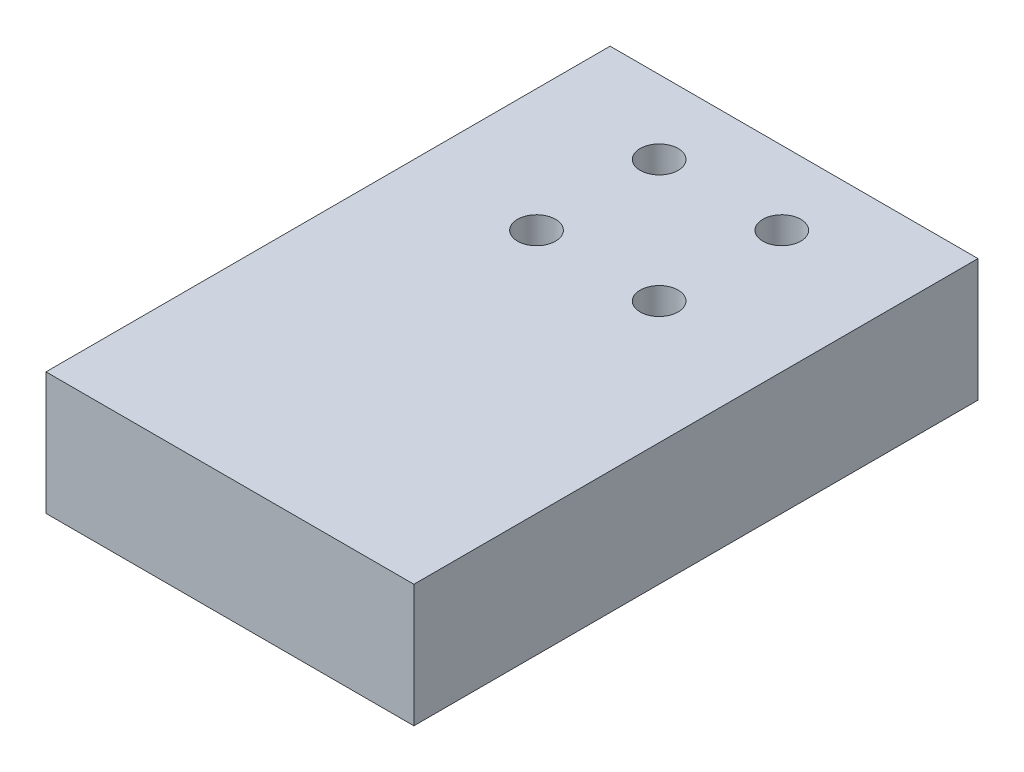
SolidWorks part; units mm, degrees
ref_plane "前视基准面" through (0, 0, 0) normal (0, 0, 1) x (1, 0, 0)
ref_plane "上视基准面" through (0, 0, 0) normal (0, 1, 0) x (1, 0, 0)
ref_plane "右视基准面" through (0, 0, 0) normal (1, 0, 0) x (0, 0, -1)
sketch "草图1" plane through (0, 0, 0) normal (0, 1, 0) x (1, 0, 0)
  line L1 (-15, -15) -> (15, -15)
  line L2 (-15, -15) -> (-15, 15)
  line L3 (-15, 15) -> (15, 15)
  line L4 (15, -15) -> (15, 15)
  line L5 (-15, -15) -> (15, 15) construction
  line L6 (-15, 15) -> (15, -15) construction
  point P0 (0, 0)
  dimension "D1" = 30
  dimension "D2" = 30
extrude "凸台-拉伸1" add sketch "草图1" along normal blind 10
sketch "草图3" plane through (0, 0, 0) normal (0, -1, 0) x (1, 0, 0)
  line L0 (0, 0) -> (0, 11.9997) construction
  line L1 (-15, -15) -> (-15, 15) construction
  line L2 (-15, 6.5) -> (15, 6.5)
  line L3 (-15, 6.5) -> (-15, 13.5)
  line L4 (-15, 13.5) -> (15, 13.5)
  line L5 (15, 6.5) -> (15, 13.5)
  line L6 (-15, 6.5) -> (15, 13.5) construction
  line L7 (-15, 13.5) -> (15, 6.5) construction
  line L9 (-15, 15) -> (15, 15)
  line L10 (-15, 15) -> (-15, 13.5)
  line L11 (-15, 13.5) -> (15, 13.5)
  line L12 (15, 15) -> (15, 13.5)
  point P3 (0, 10)
  dimension "D1" = 7
  dimension "D2" = 10
sketch "草图4" plane through (0, 0, 0) normal (0, -1, 0) x (1, 0, 0)
  line L0 (0, 0) -> (0, -15.9735) construction
  line L2 (-5, -9) -> (5, -9) construction
  line L3 (-5, -9) -> (-5, 1) construction
  line L4 (-5, 1) -> (5, 1) construction
  line L5 (5, -9) -> (5, 1) construction
  line L6 (-5, -9) -> (5, 1) construction
  line L7 (-5, 1) -> (5, -9) construction
  circle A0 centre (-5, 1) radius 1.55
  circle A1 centre (5, 1) radius 1.55
  circle A2 centre (5, -9) radius 1.55
  circle A3 centre (-5, -9) radius 1.55
  point P3 (0, -4)
  dimension "D4" = 3.1
  dimension "D1" = 10
  dimension "D2" = 10
  dimension "D3" = 4
extrude "切除-拉伸1" cut sketch "草图4" against normal blind 30 contours A1 | A2 | A0 | A3
sketch "草图5" plane through (0, 0, 0) normal (0, -1, 0) x (1, 0, 0)
  circle A0 centre (-5, 1) radius 3.5
  circle A1 centre (5, 1) radius 3.5
  circle A2 centre (-5, -9) radius 3.5
  circle A3 centre (5, -9) radius 3.5
  circle M5 centre (5, -9) radius 1.55
  circle M7 centre (-5, -9) radius 1.55
  circle M8 centre (5, 1) radius 1.55
  dimension "D1" = 7
extrude "切除-拉伸2" cut sketch "草图5" against normal blind 3 contours A1 M8 | A3 M5 | A2 M7 | A0
sketch "草图6" plane through (0, 0, 15) normal (0, 0, 1) x (1, 0, 0)
  line L1 (-15, 10) -> (15, 10)
  line L2 (-15, 10) -> (-15, 0)
  line L3 (-15, 0) -> (15, 0)
  line L4 (15, 10) -> (15, 0)
extrude "凸台-拉伸2" add sketch "草图6" along normal blind 16
